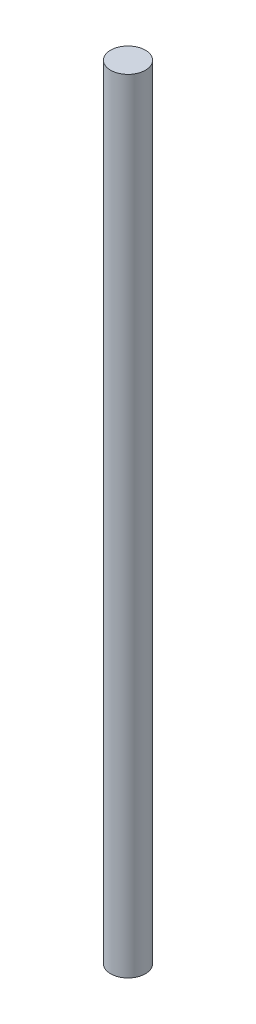
SolidWorks part; units mm, degrees
material "Brass"
ref_plane "Plan de face" through (0, 0, 0) normal (0, 0, 1) x (1, 0, 0)
ref_plane "Plan de dessus" through (0, 0, 0) normal (0, 1, 0) x (1, 0, 0)
ref_plane "Plan de droite" through (0, 0, 0) normal (1, 0, 0) x (0, 0, -1)
sketch "Sketch1" plane through (0, 0, 0) normal (0, 1, 0) x (1, 0, 0)
  circle A0 centre (0, 0) radius 1
  dimension "D1" = 2
extrude "Boss-Extrude1" add sketch "Sketch1" along normal blind 45
